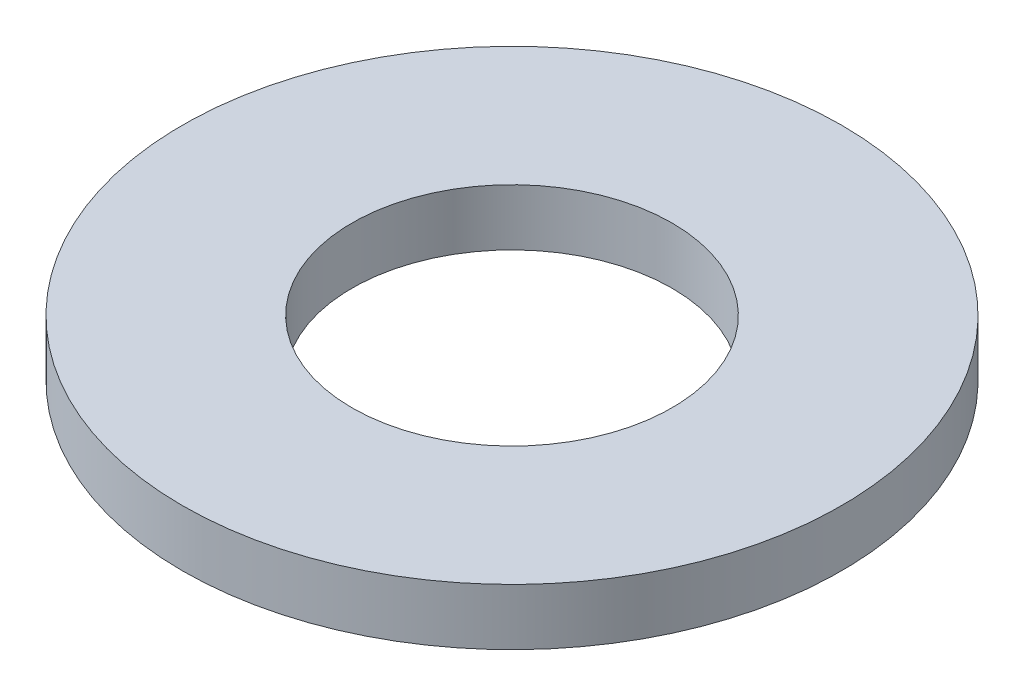
SolidWorks part; units mm, degrees
material "ASTM A36 Steel"
ref_plane "Front Plane" through (0, 0, 0) normal (0, 0, 1) x (1, 0, 0)
ref_plane "Top Plane" through (0, 0, 0) normal (0, 1, 0) x (1, 0, 0)
ref_plane "Right Plane" through (0, 0, 0) normal (1, 0, 0) x (0, 0, -1)
ref_axis "Axis1" through (0, 1.6774, 0) along (0, -1, 0)
sketch "Sketch1" plane through (0, 0, 0) normal (0, 0, 1) x (1, 0, 0)
  line L0 (0, 2.5689) -> (0, 12.8126) construction
  line L1 (0.85, 0.3) -> (1.75, 0.3)
  line L2 (0.85, 0.3) -> (0.85, 0)
  line L3 (0.85, 0) -> (1.75, 0)
  line L4 (1.75, 0.3) -> (1.75, 0)
  dimension "D1" = 1.7
  dimension "D2" = 3.5
  dimension "D3" = 0.3
revolve "Revolve1" add sketch "Sketch1" angle 360 about axis through (0, 1.6774, 0) along (0, -1, 0)
